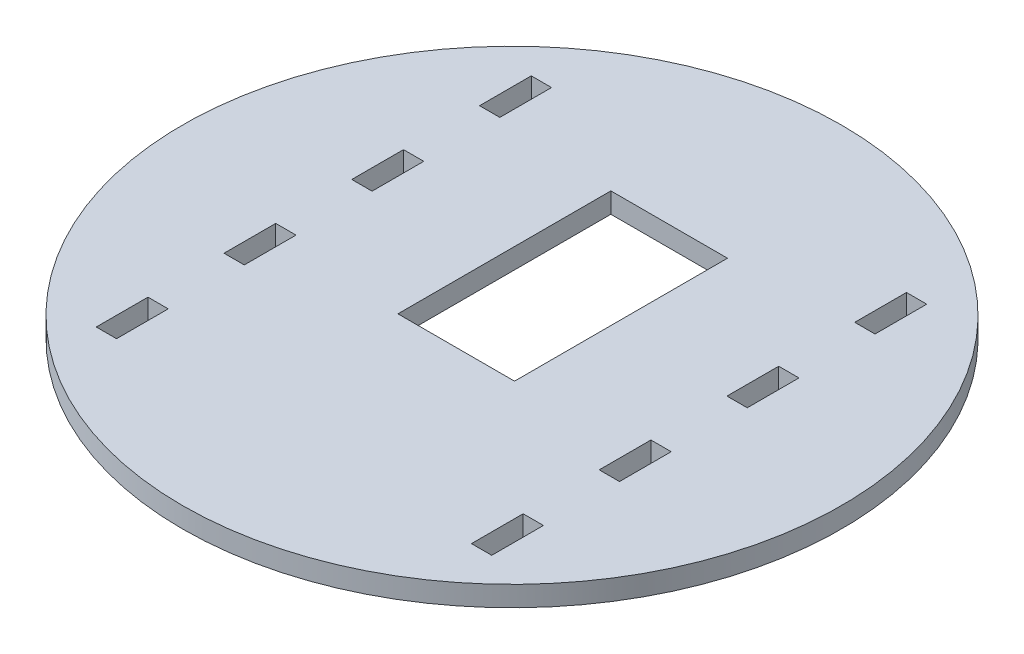
SolidWorks part; units mm, degrees
ref_plane "Alzado" through (0, 0, 0) normal (0, 0, 1) x (1, 0, 0)
ref_plane "Planta" through (0, 0, 0) normal (0, 1, 0) x (1, 0, 0)
ref_plane "Vista lateral" through (0, 0, 0) normal (1, 0, 0) x (0, 0, -1)
sketch "Croquis2" plane through (0, 0, 0) normal (0, 1, 0) x (1, 0, 0)
  line L0 (-39, 17.6) -> (-35, 17.6)
  line L1 (-39, 42.8) -> (-35, 42.8)
  line L2 (-39, 42.8) -> (-39, 32.6)
  line L3 (-39, 32.6) -> (-35, 32.6)
  line L4 (-35, 42.8) -> (-35, 32.6)
  line L5 (-39, 17.6) -> (-39, 7.4)
  line L6 (-39, 7.4) -> (-35, 7.4)
  line L7 (-35, 17.6) -> (-35, 7.4)
  line L8 (-39, -32.8) -> (-35, -32.8)
  line L9 (-39, -32.8) -> (-39, -43)
  line L10 (-39, -43) -> (-35, -43)
  line L11 (-35, -32.8) -> (-35, -43)
  line L12 (-39, -7.6) -> (-35, -7.6)
  line L13 (-39, -7.6) -> (-39, -17.8)
  line L14 (-39, -17.8) -> (-35, -17.8)
  line L15 (-35, -7.6) -> (-35, -17.8)
  line L16 (0, 0) -> (-65, 0) construction
  line L17 (0, 0) -> (0, 23.1076) construction
  line L18 (35, -32.8) -> (35, -43)
  line L19 (39, -32.8) -> (39, -43)
  line L20 (39, -43) -> (35, -43)
  line L21 (39, -32.8) -> (35, -32.8)
  line L22 (39, -17.8) -> (35, -17.8)
  line L23 (39, -7.6) -> (39, -17.8)
  line L24 (35, -7.6) -> (35, -17.8)
  line L25 (39, -7.6) -> (35, -7.6)
  line L26 (39, 7.4) -> (35, 7.4)
  line L27 (35, 42.8) -> (35, 32.6)
  line L28 (35, 17.6) -> (35, 7.4)
  line L29 (39, 17.6) -> (35, 17.6)
  line L30 (39, 17.6) -> (39, 7.4)
  line L31 (39, 32.6) -> (35, 32.6)
  line L32 (39, 42.8) -> (35, 42.8)
  line L33 (39, 42.8) -> (39, 32.6)
  circle A0 centre (0, 0) radius 65
  point P19 (-35, 12.5)
  point P22 (-37, 17.6)
  point P23 (-37, -7.6)
  dimension "D1" = 130
  dimension "D2" = 4
  dimension "D3" = 10.2
  dimension "D4" = 15
  dimension "D5" = 15
  dimension "D6" = 15
  dimension "D7" = 35
  dimension "D8" = 7.6
extrude "Saliente-Extruir1" add sketch "Croquis2" along normal blind 4 contours A0
sketch "Croquis3" plane through (0, 4, 0) normal (0, 1, 0) x (1, 0, 0)
  line L8 (-39, 7.4) -> (-35, 7.4)
  line L9 (-35, 7.4) -> (-35, 17.6)
  line L10 (-35, 17.6) -> (-39, 17.6)
  line L11 (-39, 17.6) -> (-39, 7.4)
  line L12 (-39, -7.6) -> (-35, -7.6)
  line L13 (-35, -7.6) -> (-35, -17.8)
  line L14 (-35, -17.8) -> (-39, -17.8)
  line L15 (-39, -17.8) -> (-39, -7.6)
  line L16 (-39, -32.8) -> (-35, -32.8)
  line L17 (-35, -32.8) -> (-35, -43)
  line L18 (-35, -43) -> (-39, -43)
  line L19 (-39, -43) -> (-39, -32.8)
  line L20 (-39, 42.8) -> (-35, 42.8)
  line L21 (-35, 42.8) -> (-35, 32.6)
  line L22 (-35, 32.6) -> (-39, 32.6)
  line L23 (-39, 32.6) -> (-39, 42.8)
  line L24 (0, 0) -> (0, 15.2849) construction
  line L25 (0, 0) -> (0, 23.1076) construction
  line L26 (35, 32.6) -> (39, 32.6)
  line L27 (35, 42.8) -> (35, 32.6)
  line L28 (39, 42.8) -> (35, 42.8)
  line L29 (39, 32.6) -> (39, 42.8)
  line L30 (35, 17.6) -> (39, 17.6)
  line L31 (35, 7.4) -> (35, 17.6)
  line L32 (39, 7.4) -> (35, 7.4)
  line L33 (39, 17.6) -> (39, 7.4)
  line L34 (35, -17.8) -> (39, -17.8)
  line L35 (35, -7.6) -> (35, -17.8)
  line L36 (39, -7.6) -> (35, -7.6)
  line L37 (39, -17.8) -> (39, -7.6)
  line L38 (35, -43) -> (39, -43)
  line L39 (35, -32.8) -> (35, -43)
  line L40 (39, -32.8) -> (35, -32.8)
  line L41 (39, -43) -> (39, -32.8)
extrude "Cortar-Extruir6" cut sketch "Croquis3" against normal up to next
sketch "Croquis4" plane through (0, 4, 0) normal (0, 1, 0) x (1, 0, 0)
  line L1 (11.5, -11) -> (-11.5, -11)
  line L2 (11.5, -11) -> (11.5, 31)
  line L3 (11.5, 31) -> (-11.5, 31)
  line L4 (-11.5, -11) -> (-11.5, 31)
  point P0 (0, 0)
  point P6 (0, 0)
  point P8 (-11.5, -3.3371)
  dimension "D1" = 42
  dimension "D2" = 23
  dimension "D3" = 31
  dimension "D4" = 11.5
extrude "Cortar-Extruir8" cut sketch "Croquis4" against normal blind 10
